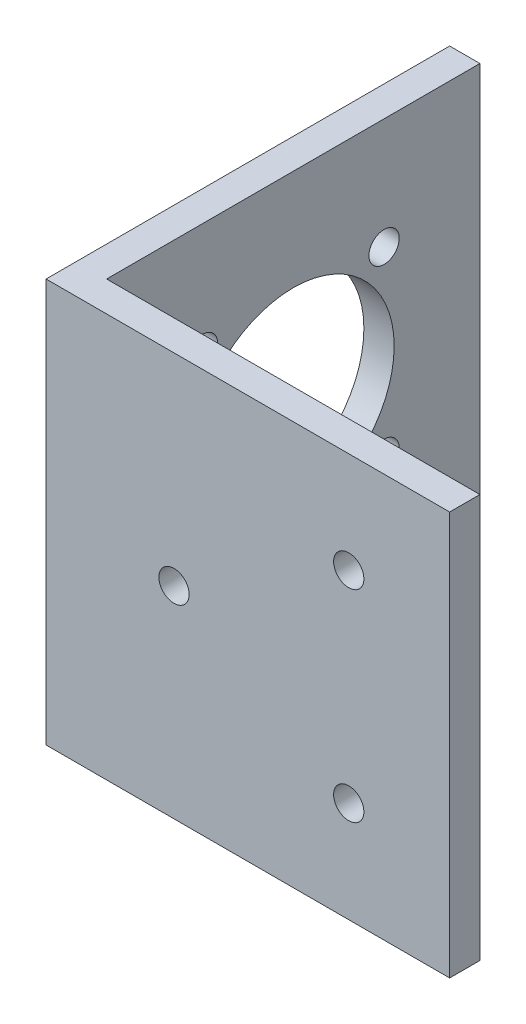
SolidWorks part; units mm, degrees
ref_plane "Спереди" through (0, 0, 0) normal (0, 0, 1) x (1, 0, 0)
ref_plane "Сверху" through (0, 0, 0) normal (0, 1, 0) x (1, 0, 0)
ref_plane "Справа" through (0, 0, 0) normal (1, 0, 0) x (0, 0, -1)
sketch "Эскиз1" plane through (0, 0, 0) normal (0, 1, 0) x (1, 0, 0)
  line L0 (0, 0) -> (40, 0)
  line L1 (40, 0) -> (40, 3)
  line L2 (40, 3) -> (3, 3)
  line L3 (3, 3) -> (3, 40)
  line L4 (3, 40) -> (0, 40)
  line L5 (0, 40) -> (0, 0)
  line L6 (1, 24.5) -> (1, 18.5) construction
  dimension "D1" = 3
  dimension "D2" = 3
  dimension "D3" = 40
  dimension "D4" = 40
  dimension "D5" = 37
extrude "Бобышка-Вытянуть1" add sketch "Эскиз1" along normal blind 40
sketch "Эскиз2" plane through (3, 0, 0) normal (1, 0, 0) x (0, 0, -1)
  line L0 (40, 0) -> (3, 40) construction
  line L1 (3, 0) -> (40, 40) construction
  line L3 (30.5, 29) -> (12.5, 29) construction
  line L4 (30.5, 29) -> (30.5, 11) construction
  line L5 (30.5, 11) -> (12.5, 11) construction
  line L6 (12.5, 29) -> (12.5, 11) construction
  line L7 (30.5, 29) -> (12.5, 11) construction
  line L8 (30.5, 11) -> (12.5, 29) construction
  circle A0 centre (21.5, 20) radius 10
  circle A1 centre (30.5, 29) radius 1.5
  circle A2 centre (30.5, 11) radius 1.5
  circle A3 centre (12.5, 11) radius 1.5
  circle A4 centre (12.5, 29) radius 1.5
  dimension "D1" = 20
  dimension "D4" = 3
  dimension "D2" = 18
  dimension "D3" = 18
extrude "Вырез-Вытянуть1" cut sketch "Эскиз2" against normal blind 40
sketch "Эскиз3" plane through (0, 0, -3) normal (0, 0, -1) x (-1, 0, 0)
  line L0 (-30, 30) -> (-12.6795, 20) construction
  line L1 (-12.6795, 20) -> (-30, 10) construction
  line L2 (-30, 10) -> (-30, 30) construction
  line L3 (-30, 30) -> (-30, 40) construction
  line L4 (-40, 40) -> (-3, 40) construction
  line L5 (-30, 10) -> (-30, 0) construction
  line L6 (-40, 0) -> (-3, 0) construction
  line L7 (-30, 30) -> (-40, 30) construction
  line L8 (-40, 40) -> (-40, 0) construction
  line L9 (-12.6795, 20) -> (-3, 20) construction
  line L11 (-3, 40) -> (-3, 0) construction
  line L13 (0, 27.3574) -> (0, -9.8073) construction
  circle A0 centre (-30, 30) radius 1.5
  circle A1 centre (-12.6795, 20) radius 1.5
  circle A2 centre (-30, 10) radius 1.5
  dimension "D1" = 3
  dimension "D2" = 60
  dimension "D3" = 60
  dimension "D4" = 10
  dimension "D5" = 20
  dimension "D7" = 12.6795
extrude "Вырез-Вытянуть2" cut sketch "Эскиз3" against normal through all
